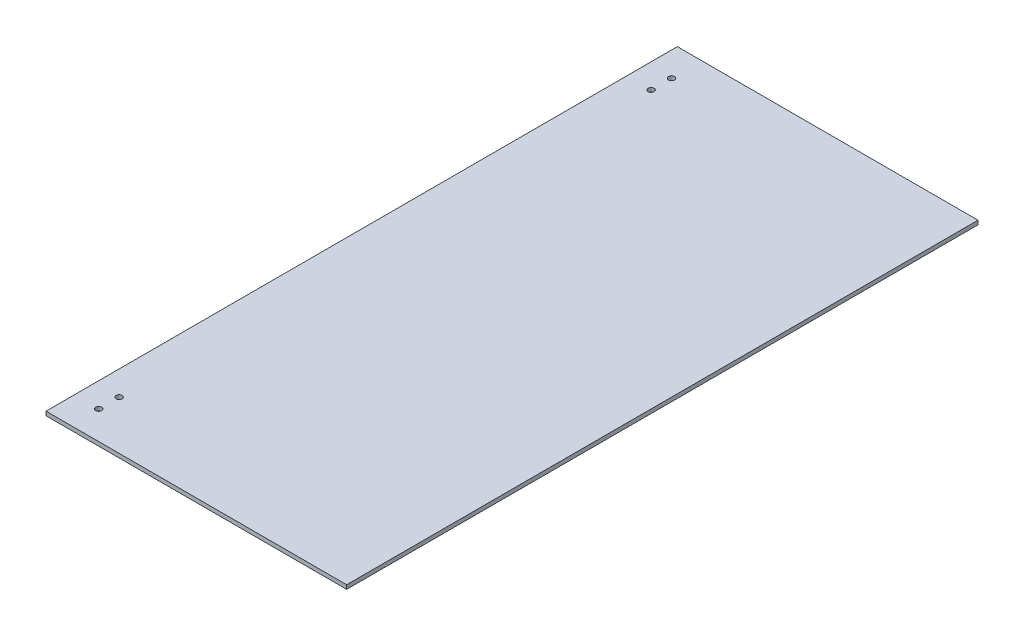
SolidWorks part; units mm, degrees
ref_plane "Front Plane" through (0, 0, 0) normal (0, 0, 1) x (1, 0, 0)
ref_plane "Top Plane" through (0, 0, 0) normal (0, 1, 0) x (1, 0, 0)
ref_plane "Right Plane" through (0, 0, 0) normal (1, 0, 0) x (0, 0, -1)
sketch "Sketch1" plane through (0, 0, 0) normal (0, 1, 0) x (1, 0, 0)
  line L1 (-75, 157.5) -> (75, 157.5)
  line L2 (-75, 157.5) -> (-75, -157.5)
  line L3 (-75, -157.5) -> (75, -157.5)
  line L4 (75, 157.5) -> (75, -157.5)
  line L5 (-75, 157.5) -> (75, -157.5) construction
  line L6 (-75, -157.5) -> (75, 157.5) construction
  point P0 (0, 0)
extrude "Boss-Extrude1" add sketch "Sketch1" along normal blind 2
sketch "Sketch2" plane through (0, 2, 0) normal (0, 1, 0) x (1, 0, 0)
  circle A0 centre (-62.8273, -143.3786) radius 1.5
  circle A1 centre (-62.8273, -133.206) radius 1.5
  circle A2 centre (-62.8273, 132.2326) radius 1.5
  circle A3 centre (-62.8273, 142.4051) radius 1.5
extrude "Cut-Extrude1" cut sketch "Sketch2" against normal through all
